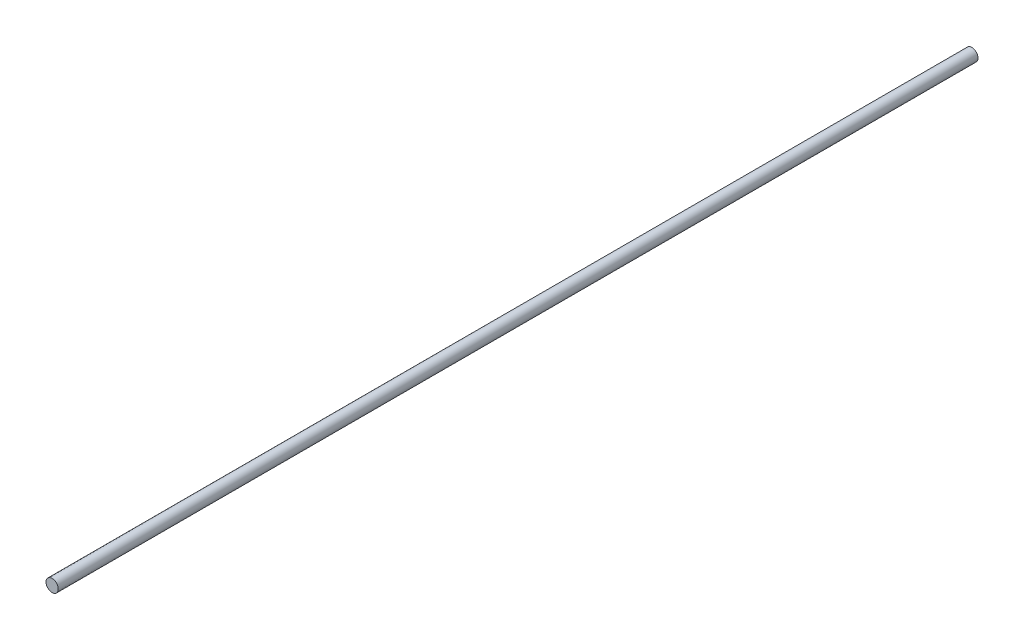
SolidWorks part; units mm, degrees
ref_plane "前视基准面" through (0, 0, 0) normal (0, 0, 1) x (1, 0, 0)
ref_plane "上视基准面" through (0, 0, 0) normal (0, 1, 0) x (1, 0, 0)
ref_plane "右视基准面" through (0, 0, 0) normal (1, 0, 0) x (0, 0, -1)
sketch "草图1" plane through (0, 0, 0) normal (0, 0, 1) x (1, 0, 0)
  circle A0 centre (0, 0) radius 4
  dimension "D1" = 8
extrude "凸台-拉伸1" add sketch "草图1" along normal mid plane 600
